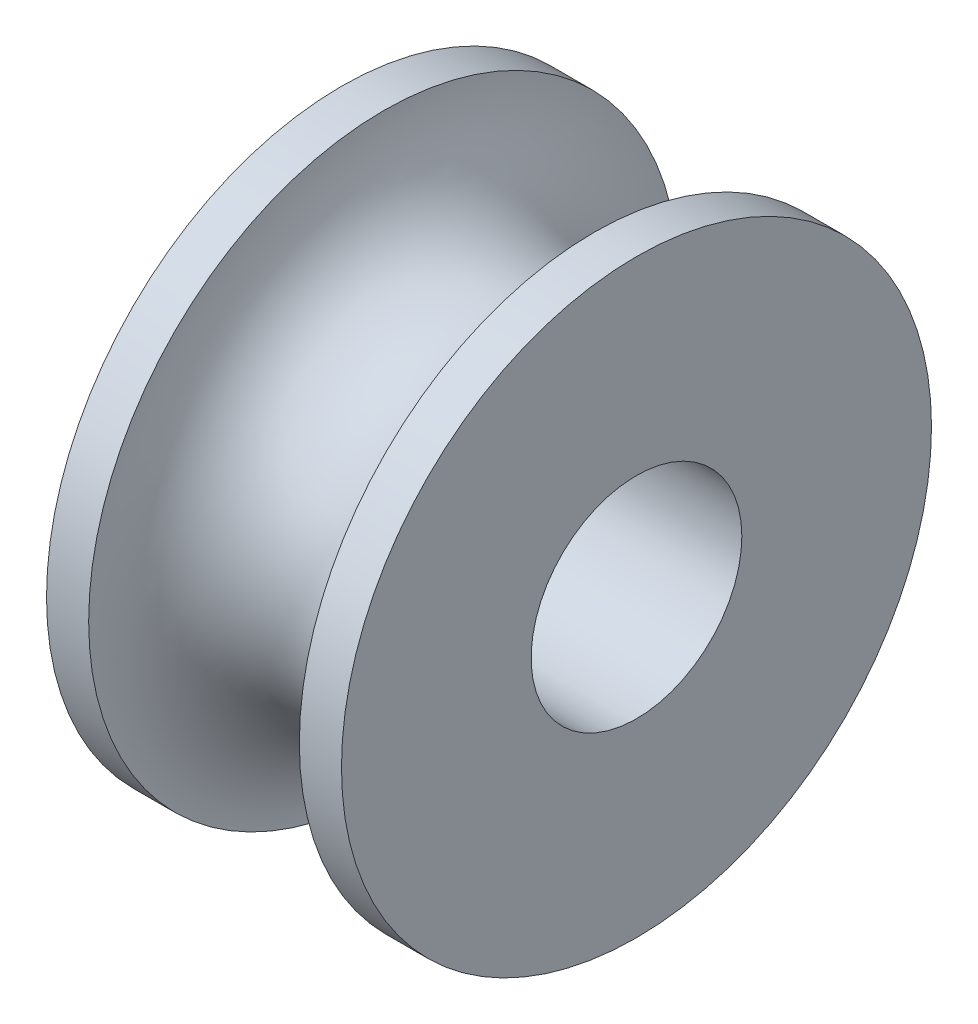
SolidWorks part; units mm, degrees
ref_plane "Front Plane" through (0, 0, 0) normal (0, 0, 1) x (1, 0, 0)
ref_plane "Top Plane" through (0, 0, 0) normal (0, 1, 0) x (1, 0, 0)
ref_plane "Right Plane" through (0, 0, 0) normal (1, 0, 0) x (0, 0, -1)
sketch "Sketch1" plane through (0, 0, 0) normal (0, 0, 1) x (1, 0, 0)
  line L0 (0, 0) -> (-8989.7386, 0) construction
  line L1 (0, 2.5) -> (6.9989, 2.5)
  line L5 (0, 2.5) -> (0, 7)
  line L8 (0, 7) -> (1, 7)
  line L9 (6.9989, 7) -> (5.9989, 7)
  line L10 (3.4994, 6.9468) -> (3.4994, 2.5) construction
  line L11 (6.9989, 7) -> (6.9989, 2.5)
  arc A0 (1, 7) -> (5.9989, 7) centre (3.4994, 6.9468) ccw
  point P15 (3.4994, 2.5)
  dimension "D1" = 2.5
  dimension "D2" = 4.9989
  dimension "D3" = 1
  dimension "D4" = 1
  dimension "D5" = 2.5
  dimension "D6" = 4.5
revolve "Revolve1" add sketch "Sketch1" angle 360 about L0
